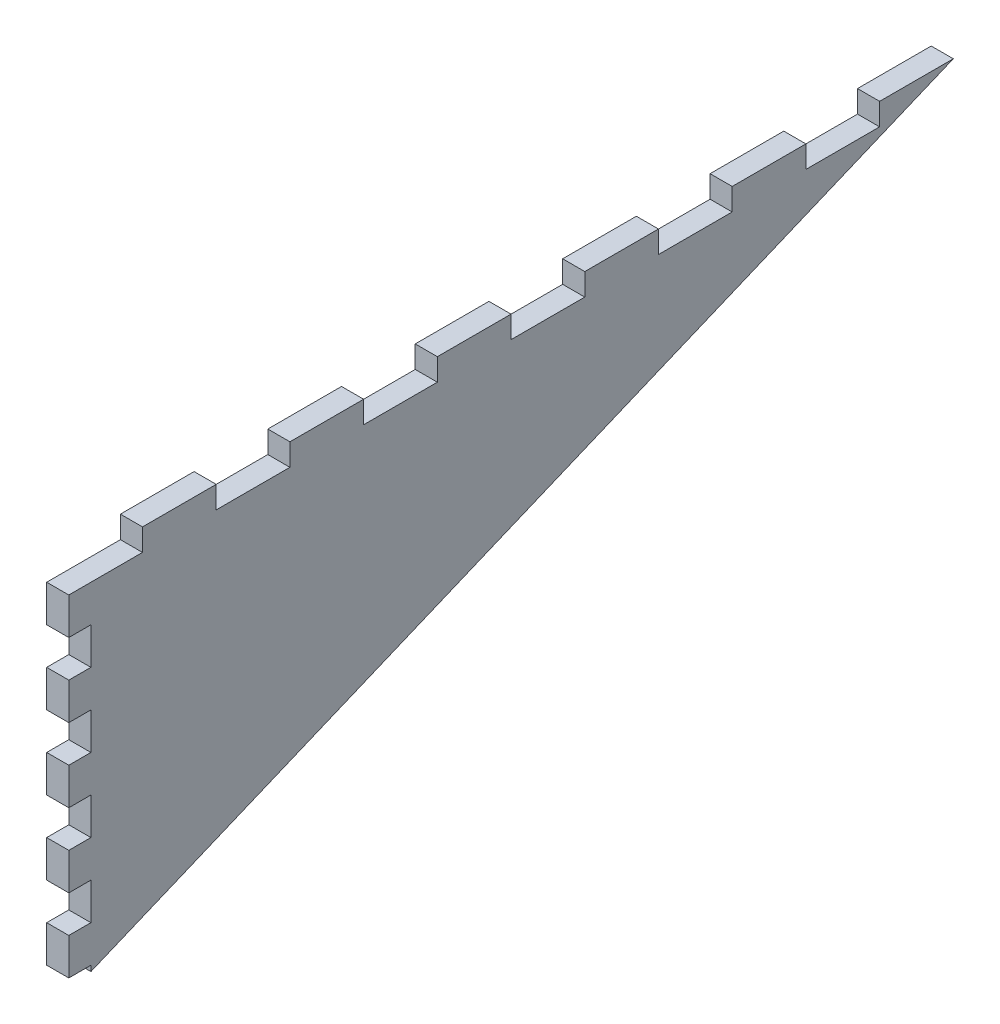
SolidWorks part; units mm, degrees
material "Beech"
ref_plane "Front Plane" through (0, 0, 0) normal (0, 0, 1) x (1, 0, 0)
ref_plane "Top Plane" through (0, 0, 0) normal (0, 1, 0) x (1, 0, 0)
ref_plane "Right Plane" through (0, 0, 0) normal (1, 0, 0) x (0, 0, -1)
sketch "Sketch1" plane through (0, 0, 0) normal (1, 0, 0) x (0, 0, -1)
  line L0 (0, 0) -> (0, -50)
  line L1 (0, -50) -> (120, 0)
  line L2 (120, 0) -> (0, 0)
  line L3 (0, -8) -> (3, -8)
  line L4 (3, -8) -> (3, -13)
  line L5 (3, -13) -> (0, -13)
  line L6 (0, -18) -> (3, -18)
  line L7 (3, -23) -> (0, -23)
  line L8 (3, -18) -> (3, -23)
  line L9 (0, -28) -> (3, -28)
  line L10 (3, -33) -> (0, -33)
  line L11 (3, -28) -> (3, -33)
  line L12 (0, -38) -> (3, -38)
  line L13 (3, -43) -> (0, -43)
  line L14 (3, -38) -> (3, -43)
  line L15 (10, 0) -> (10, -3)
  line L16 (10, -3) -> (20, -3)
  line L17 (20, -3) -> (20, 0)
  line L18 (30, 0) -> (30, -3)
  line L19 (30, -3) -> (40, -3)
  line L20 (40, -3) -> (40, 0)
  line L21 (50, 0) -> (50, -3)
  line L22 (50, -3) -> (60, -3)
  line L23 (60, -3) -> (60, 0)
  line L24 (70, 0) -> (70, -3)
  line L25 (70, -3) -> (80, -3)
  line L26 (80, -3) -> (80, 0)
  line L27 (90, 0) -> (90, -3)
  line L28 (90, -3) -> (100, -3)
  line L29 (100, -3) -> (100, 0)
  line L30 (110, 0) -> (110, -3)
  line L31 (110, -3) -> (120, -3)
  line L32 (120, -3) -> (120, 0)
  line L33 (0, -48) -> (3, -48)
  line L34 (3, -53) -> (0, -53)
  line L35 (3, -48) -> (3, -53)
  line L36 (10, -3) -> (0, -3)
  line L37 (20, -3) -> (30, -3)
  line L38 (40, -3) -> (50, -3)
  line L39 (60, -3) -> (70, -3)
  line L40 (80, -3) -> (90, -3)
  line L41 (100, -3) -> (110, -3)
  dimension "D1" = 50
  dimension "D2" = 120
  dimension "D3" = 3
  dimension "D4" = 5
  dimension "D5" = 8
  dimension "D7" = 3
  dimension "D8" = 10
  dimension "D9" = 10
  dimension "D6" = 5
  dimension "D10" = 6
extrude "Boss-Extrude1" add sketch "Sketch1" along normal blind 3 contours L31 L30 L2 L29 L28 L27 L26 L25 L24 L23 L22 L21 L20 L19 L18 L17 L16 L15 L0 L3 L4 L5 L6 L8 L7 L9 L11 L10 L12 L14 L1 | L16 L17 L2 L15 | L19 L20 L2 L18 | L22 L23 L2 L21 | L25 L26 L2 L24 | L28 L29 L2 L27 | L30 L31 L1 L2
